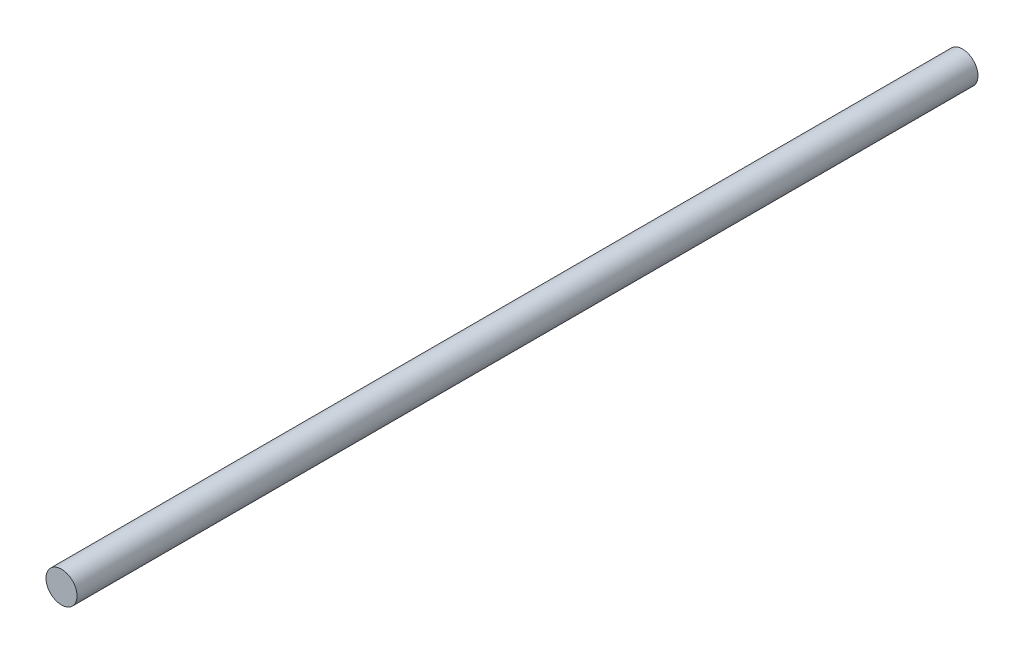
SolidWorks part; units mm, degrees
material "1.7036 (28CrS4)"
ref_plane "정면" through (0, 0, 0) normal (0, 0, 1) x (1, 0, 0)
ref_plane "윗면" through (0, 0, 0) normal (0, 1, 0) x (1, 0, 0)
ref_plane "우측면" through (0, 0, 0) normal (1, 0, 0) x (0, 0, -1)
sketch "스케치1" plane through (0, 0, 0) normal (0, 0, 1) x (1, 0, 0)
  circle A0 centre (0, 0) radius 5
  dimension "D1" = 10
extrude "보스-돌출1" add sketch "스케치1" along normal blind 290
sketch "스케치2" plane through (0, 0, 290) normal (0, 0, 1) x (1, 0, 0)
  text T0 "TEST\r\n"
equation "\"`\"=4"
